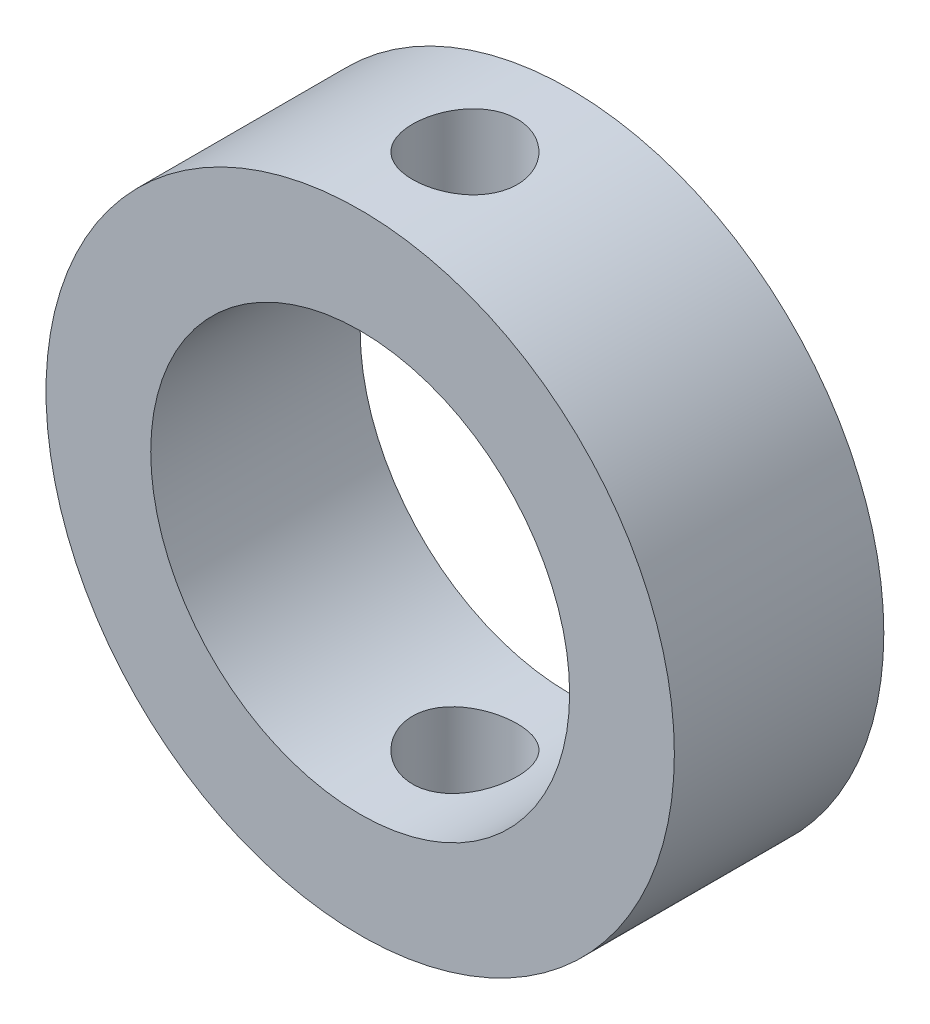
SolidWorks part; units mm, degrees
ref_plane "Front Plane" through (0, 0, 0) normal (0, 0, 1) x (1, 0, 0)
ref_plane "Top Plane" through (0, 0, 0) normal (0, 1, 0) x (1, 0, 0)
ref_plane "Right Plane" through (0, 0, 0) normal (1, 0, 0) x (0, 0, -1)
sketch "Sketch1" plane through (0, 0, 0) normal (0, 0, 1) x (1, 0, 0)
  circle A1 centre (0, 1.1599) radius 15
  circle A2 centre (0, 1.1599) radius 10
extrude "Boss-Extrude1" add sketch "Sketch1" along normal blind 10
sketch "Sketch2" plane through (0, 0, 0) normal (0, 1, 0) x (1, 0, 0)
  circle A0 centre (0, -5) radius 2.5
  point P11 (0, -5)
extrude "Cut-Extrude1" cut sketch "Sketch2" against normal blind 19 and the other way blind 21
